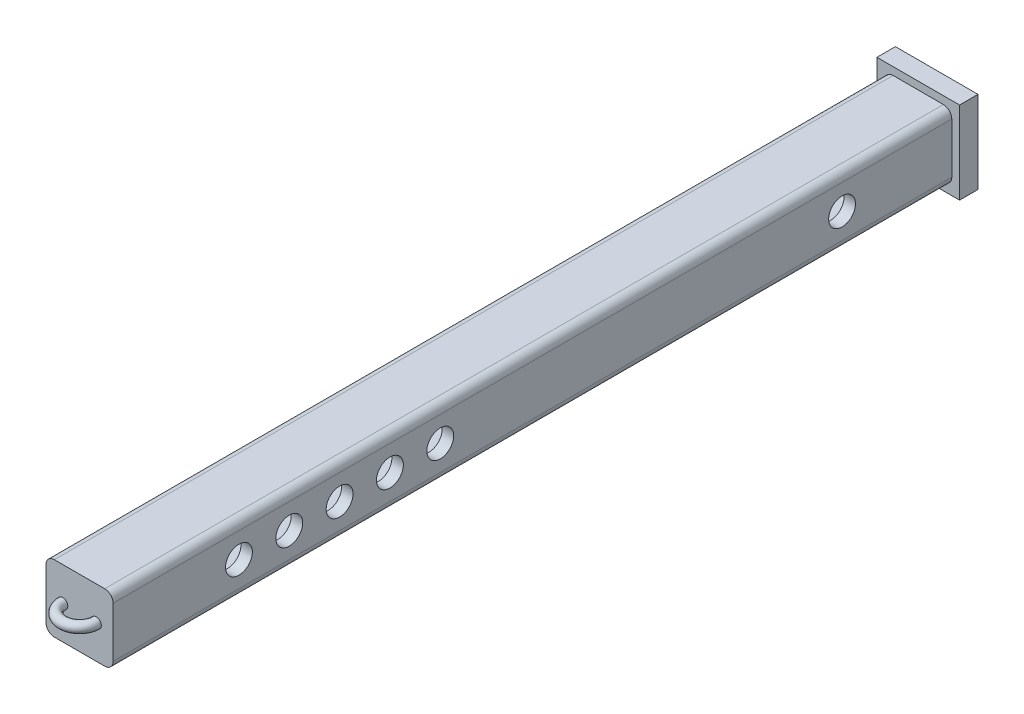
SolidWorks part; units mm, degrees
ref_plane "Front Plane" through (0, 0, 0) normal (0, 0, 1) x (1, 0, 0)
ref_plane "Top Plane" through (0, 0, 0) normal (0, 1, 0) x (1, 0, 0)
ref_plane "Right Plane" through (0, 0, 0) normal (1, 0, 0) x (0, 0, -1)
sketch "Sketch1" plane through (0, 0, 0) normal (0, 0, 1) x (1, 0, 0)
  line L1 (-20, -20) -> (20, -20)
  line L2 (-20, -20) -> (-20, 20)
  line L3 (-20, 20) -> (20, 20)
  line L4 (20, -20) -> (20, 20)
  point P0 (0, 0)
  dimension "D1" = 40
  dimension "D2" = 40
extrude "Boss-Extrude1" add sketch "Sketch1" along normal blind 500
sketch "Sketch2" plane through (0, 0, 500) normal (0, 0, 1) x (1, 0, 0)
  line L0 (0, 23.4958) -> (0, -29.8657) construction
  circle A0 centre (-10, 0) radius 3
  circle A1 centre (10, 0) radius 3
  dimension "D1" = 6
  dimension "D2" = 6
  dimension "D3" = 10
  dimension "D4" = 10
revolve "Revolve1" add sketch "Sketch2" angle 360 about L0
fillet "Fillet1" radius 5 4 edges at (20, -20, 250) (-20, -20, 250) (-20, 20, 250) (20, 20, 250)
sketch "Sketch4" plane through (0, 0, 0) normal (0, 0, -1) x (-1, 0, 0)
  line L1 (-13.1597, -13.5183) -> (13.1597, -13.5183)
  line L2 (-13.1597, -13.5183) -> (-13.1597, 13.5183)
  line L3 (-13.1597, 13.5183) -> (13.1597, 13.5183)
  line L4 (13.1597, -13.5183) -> (13.1597, 13.5183)
  line L5 (-13.1597, -13.5183) -> (13.1597, 13.5183) construction
  line L6 (-13.1597, 13.5183) -> (13.1597, -13.5183) construction
  point P0 (0, 0)
extrude "Cut-Extrude1" cut sketch "Sketch4" against normal blind 484
sketch "Sketch5" plane through (0, 0, 0) normal (0, 0, -1) x (-1, 0, 0)
  line L1 (24.6272, -24.5713) -> (-24.6272, -24.5713)
  line L2 (24.6272, -24.5713) -> (24.6272, 24.5713)
  line L3 (24.6272, 24.5713) -> (-24.6272, 24.5713)
  line L4 (-24.6272, -24.5713) -> (-24.6272, 24.5713)
  line L5 (24.6272, -24.5713) -> (-24.6272, 24.5713) construction
  line L6 (24.6272, 24.5713) -> (-24.6272, -24.5713) construction
  point P0 (0, 0)
extrude "Boss-Extrude3" add sketch "Sketch5" along normal blind 11
sketch "Sketch6" plane through (20, 0, 0) normal (1, 0, 0) x (0, 0, -1)
  circle A0 centre (-65.3992, 0) radius 8
  circle A1 centre (-304.9687, 0) radius 8
  circle A2 centre (-334.9687, 0) radius 8
  circle A3 centre (-364.9687, 0) radius 8
  circle A4 centre (-394.9687, 0) radius 8
  circle A5 centre (-424.9687, 0) radius 8
  dimension "D1" = 16
  dimension "D2" = 5
extrude "Cut-Extrude2" cut sketch "Sketch6" against normal blind 149
